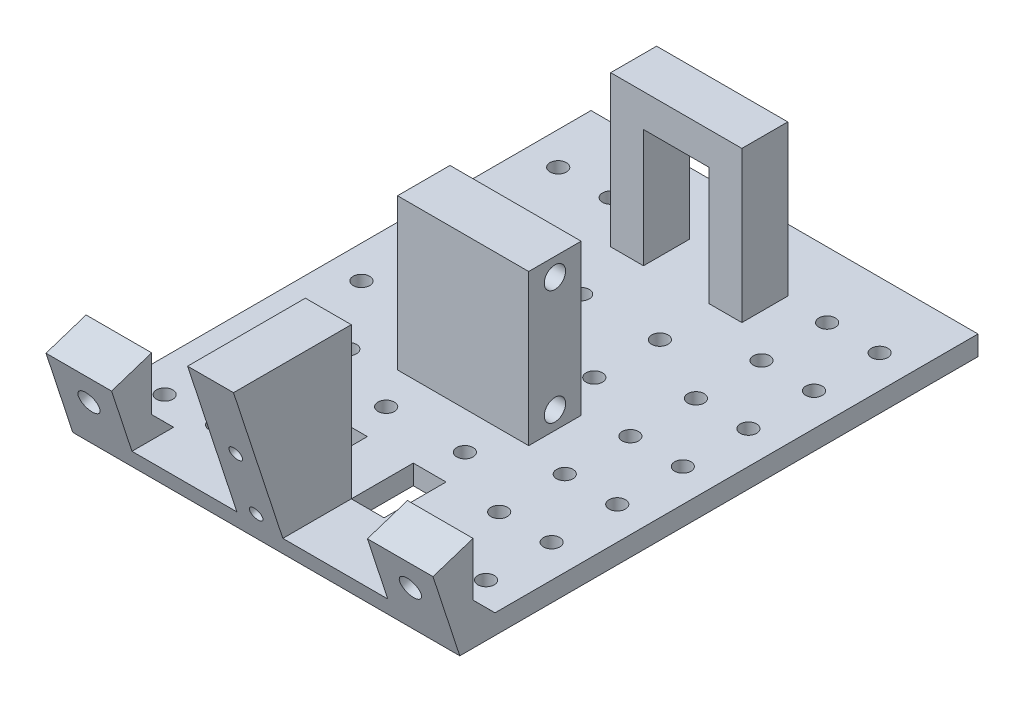
SolidWorks part; units mm, degrees
ref_plane "Alzado" through (0, 0, 0) normal (0, 0, 1) x (1, 0, 0)
ref_plane "Planta" through (0, 0, 0) normal (0, 1, 0) x (1, 0, 0)
ref_plane "Vista lateral" through (0, 0, 0) normal (1, 0, 0) x (0, 0, -1)
sketch "Croquis1" plane through (0, 0, 0) normal (0, 1, 0) x (1, 0, 0)
  line L0 (-29.5, 32.6406) -> (29.5, 32.6406)
  line L1 (29.5, 32.6406) -> (29.5, -47.3594)
  line L2 (29.5, -47.3594) -> (8.5, -47.3594)
  line L3 (8.5, -47.3594) -> (8.5, -27.4531)
  line L4 (8.5, -27.4531) -> (3.5, -27.4531)
  line L5 (3.5, -27.4531) -> (3.5, -47.3594)
  line L6 (3.5, -47.3594) -> (-3.5, -47.3594)
  line L7 (-3.5, -47.3594) -> (-3.5, -27.4531)
  line L8 (-3.5, -27.4531) -> (-8.5, -27.4531)
  line L9 (-8.5, -27.4531) -> (-8.5, -47.3594)
  line L10 (-8.5, -47.3594) -> (-29.5, -47.3594)
  line L11 (-29.5, -47.3594) -> (-29.5, 32.6406)
  line L12 (2, -7.3594) -> (47.9375, -7.3594) construction
  line L13 (0, 0) -> (0, 41.2344) construction
  dimension "D1" = 3.5
  dimension "D2" = 3.5
  dimension "D3" = 5
  dimension "D4" = 5
  dimension "D5" = 21
  dimension "D6" = 21
  dimension "D7" = 40
  dimension "D8" = 40
extrude "Saliente-Extruir1" add sketch "Croquis1" along normal blind 3
sketch "Sketch1" plane through (0, 3, 0) normal (0, 1, 0) x (1, 0, 0)
  line L0 (29.5, 32.6406) -> (-29.5, 32.6406) construction
  line L1 (-10, 23.1406) -> (10, 23.1406)
  line L2 (-10, 23.1406) -> (-10, 16.1406)
  line L3 (-10, 16.1406) -> (10, 16.1406)
  line L4 (10, 23.1406) -> (10, 16.1406)
  line L5 (-10, -8.3594) -> (10, -8.3594)
  line L6 (-10, -8.3594) -> (-10, -16.3594)
  line L7 (-10, -16.3594) -> (10, -16.3594)
  line L8 (10, -8.3594) -> (10, -16.3594)
  line L9 (0, 32.6406) -> (0, -23.7131) construction
  line L10 (8.5, -47.3594) -> (29.5, -47.3594) construction
  line L11 (3.5, -16.3594) -> (-3.5, -16.3594)
  line L12 (3.5, -16.3594) -> (3.5, -54.8594)
  line L13 (3.5, -54.8594) -> (-3.5, -54.8594)
  line L14 (-3.5, -16.3594) -> (-3.5, -54.8594)
  dimension "D1" = 9.5
  dimension "D2" = 7
  dimension "D3" = 10
  dimension "D4" = 10
  dimension "D5" = 24.5
  dimension "D6" = 8
  dimension "D7" = 10
  dimension "D8" = 10
  dimension "D9" = 7.5
extrude "Boss-Extrude1" add sketch "Sketch1" along normal blind 23 contours L9 L5 L6 L7 | L5 L9 L11 L7 L8 | L1 L9 L3 L4 | L9 L1 L2 L3
sketch "Sketch2" plane through (29.5, 0, 0) normal (1, 0, 0) x (0, 0, -1)
  line L0 (-54.8594, 26) -> (-46.3594, 0)
  line L1 (-47.3594, 0) -> (32.6406, 0) construction
  line L2 (-47.3594, 0) -> (-46.3594, 0)
  line L3 (-47.3594, 0) -> (-47.3594, 3)
  line L4 (-47.3594, 3) -> (-54.8594, 3)
  line L5 (-54.8594, 26) -> (-54.8594, 3)
  dimension "D1" = 1
extrude "Cut-Extrude1" cut sketch "Sketch2" against normal through all
sketch "Sketch3" plane through (-10, 0, 0) normal (-1, 0, 0) x (0, 0, 1)
  line L0 (8.3594, 3) -> (16.3594, 3) construction
  line L1 (16.3594, 26) -> (16.3594, 3) construction
  circle A0 centre (12.3594, 5.75) radius 1.625
  circle A1 centre (12.3594, 23.25) radius 1.625
  dimension "D1" = 3.25
  dimension "D2" = 3.25
  dimension "D3" = 2.75
  dimension "D4" = 4
  dimension "D5" = 17.5
extrude "Cut-Extrude2" cut sketch "Sketch3" against normal through all
sketch "Sketch4" plane through (0, -13.6925, 41.883) normal (0, -0.3107, 0.9505) x (1, 0, 0)
  line L0 (-3.5, 14.4057) -> (3.5, 14.4057) construction
  circle A0 centre (0, 19.4057) radius 1
  circle A1 centre (0, 29.4057) radius 1
  dimension "D1" = 2
  dimension "D2" = 2
  dimension "D3" = 5
  dimension "D4" = 10
extrude "Cut-Extrude3" cut sketch "Sketch4" against normal blind 4
sketch "Croquis2" plane through (0, 0, -23.1406) normal (0, 0, -1) x (-1, 0, 0)
  line L0 (-10, 26) -> (-10, 3) construction
  line L1 (-5, 6) -> (-5, 3)
  line L2 (-5, 6) -> (-5, 21)
  line L3 (-5, 21) -> (5, 21)
  line L4 (5, 6) -> (5, 21)
  line L5 (10, 26) -> (10, 3) construction
  line L6 (10, 26) -> (-10, 26) construction
  line L7 (10, 3) -> (-10, 3) construction
  line L8 (5, 6) -> (5, 3)
  line L9 (5, 3) -> (-5, 3)
  dimension "D1" = 5
  dimension "D2" = 5
  dimension "D3" = 5
  dimension "D4" = 3
extrude "Cortar-Extruir1" cut sketch "Croquis2" against normal blind 10
sketch "Croquis3" plane through (-3.5, 0, 0) normal (-1, 0, 0) x (0, 0, 1)
  line L1 (21.9062, 3) -> (36.9062, 3)
  line L2 (21.9062, 26) -> (16.3594, 26)
  line L3 (21.9062, 26) -> (36.9062, 26)
  line L4 (36.9062, 3) -> (36.9062, 26)
  line L5 (16.3594, 26) -> (54.8594, 26) construction
  line L7 (16.3594, 26) -> (16.3594, 3)
  line L8 (16.3594, 3) -> (21.9062, 3)
  dimension "D1" = 15
extrude "Cortar-Extruir2" cut sketch "Croquis3" against normal up to next
sketch "Croquis4" plane through (0, 0, 0) normal (0, -1, 0) x (1, 0, 0)
  line L0 (-29.5, -32.6406) -> (-29.5, 46.3594) construction
  line L1 (29.5, -32.6406) -> (-29.5, -32.6406) construction
  line L2 (0, -32.6406) -> (0, 46.3594) construction
  line L4 (-10, 8.3594) -> (10, 8.3594) construction
  circle A0 centre (-24.5, -22.6406) radius 1.25
  circle A1 centre (-16.5, -22.6406) radius 1.25
  circle A2 centre (-16.5, -12.6406) radius 1.25
  circle A3 centre (-16.5, -2.6406) radius 1.25
  circle A4 centre (-16.5, 7.3594) radius 1.25
  circle A5 centre (-16.5, 17.3594) radius 1.25
  circle A6 centre (-16.5, 27.3594) radius 1.25
  circle A7 centre (-16.5, 37.3594) radius 1.25
  circle A8 centre (-24.5, -12.6406) radius 1.25
  circle A9 centre (-24.5, -2.6406) radius 1.25
  circle A10 centre (-24.5, 7.3594) radius 1.25
  circle A11 centre (-24.5, 17.3594) radius 1.25
  circle A12 centre (-24.5, 27.3594) radius 1.25
  circle A13 centre (-24.5, 37.3594) radius 1.25
  circle A14 centre (16.5, 37.3594) radius 1.25
  circle A15 centre (24.5, 37.3594) radius 1.25
  circle A16 centre (16.5, 27.3594) radius 1.25
  circle A17 centre (24.5, 27.3594) radius 1.25
  circle A18 centre (16.5, 17.3594) radius 1.25
  circle A19 centre (24.5, 17.3594) radius 1.25
  circle A20 centre (24.5, 7.3594) radius 1.25
  circle A21 centre (16.5, 7.3594) radius 1.25
  circle A22 centre (16.5, -2.6406) radius 1.25
  circle A23 centre (24.5, -2.6406) radius 1.25
  circle A24 centre (24.5, -12.6406) radius 1.25
  circle A25 centre (16.5, -12.6406) radius 1.25
  circle A26 centre (16.5, -22.6406) radius 1.25
  circle A27 centre (24.5, -22.6406) radius 1.25
  circle A28 centre (6, 22.0845) radius 1.25
  circle A29 centre (-6, 22.0845) radius 1.25
  circle A30 centre (6, 2.3594) radius 1.25
  circle A31 centre (-6, 2.3594) radius 1.25
  circle A32 centre (-6, -7.6406) radius 1.25
  circle A33 centre (6, -7.6406) radius 1.25
  dimension "D1" = 2.5
  dimension "D6" = 2.5
  dimension "D8" = 2.5
  dimension "D2" = 5
  dimension "D3" = 10
  dimension "D7" = 6
  dimension "D9" = 6
  dimension "D4" = 2
  dimension "D5" = 7
  dimension "D10" = 2
  dimension "D11" = 2
extrude "Cortar-Extruir3" cut sketch "Croquis4" against normal up to next (3 mm away)
sketch "Sketch5" plane through (-8.5, 0, 0) normal (1, 0, 0) x (0, 0, -1)
  line L0 (-36.9062, 3) -> (-36.9062, 0)
  line L1 (-46.3594, 0) -> (32.6406, 0) construction
  line L2 (-36.9062, 0) -> (-46.3594, 0)
  line L3 (-46.3594, 0) -> (-47.3401, 3)
  line L4 (-47.3401, 3) -> (-36.9062, 3)
extrude "Boss-Extrude2" add sketch "Sketch5" along normal blind 20
sketch "Croquis6" plane through (-29.5, 0, 0) normal (-1, 0, 0) x (0, 0, 1)
  line L0 (47.3401, 3) -> (50.4475, 12.505)
  line L1 (47.3401, 3) -> (54.8594, 26) construction
  line L2 (50.4475, 12.505) -> (44.3401, 14.5016)
  line L3 (44.3401, 14.5016) -> (44.3401, 3)
  line L4 (47.3401, 3) -> (36.9062, 3) construction
  line L5 (44.3401, 3) -> (47.3401, 3)
  line L6 (44.3401, 6.348) -> (40.9901, 3)
  line L7 (-32.6406, 3) -> (47.3401, 3) construction
  line L8 (40.9901, 3) -> (44.3401, 3)
  line L9 (48.8938, 7.7525) -> (39.3394, 10.876) construction
  line L10 (44.3401, 6.348) -> (45.1947, 8.9618) construction
  line M3 (47.3401, 3) -> (-32.6406, 3)
  dimension "D1" = 10
  dimension "D2" = 3
  dimension "D3" = 2.75
  dimension "D4" = 3.348
  dimension "D5" = 3.35
extrude "Saliente-Extruir2" add sketch "Croquis6" against normal blind 10 contours L2 L3 L0 M3 | L3 L6 M3
sketch "Croquis7" plane through (0, -13.6925, 41.883) normal (0, -0.3107, 0.9505) x (1, 0, 0)
  circle A0 centre (-24.5, 22.5619) radius 1.625
  dimension "D1" = 3.25
extrude "Cortar-Extruir4" cut sketch "Croquis7" against normal up to next
sketch "Croquis8" plane through (0, -13.6925, 41.883) normal (0, -0.3107, 0.9505) x (1, 0, 0)
  line L1 (-22.9123, 19.8119) -> (-21.3246, 22.5619)
  line L2 (-21.3246, 22.5619) -> (-22.9123, 25.3119)
  line L3 (-22.9123, 25.3119) -> (-26.0877, 25.3119)
  line L4 (-26.0877, 25.3119) -> (-27.6754, 22.5619)
  line L5 (-27.6754, 22.5619) -> (-26.0877, 19.8119)
  line L6 (-26.0877, 19.8119) -> (-22.9123, 19.8119)
  circle A0 centre (-24.5, 22.5619) radius 2.75 construction
  dimension "D1" = 5.5
extrude "Cortar-Extruir5" cut sketch "Croquis8" along normal blind 4 from vertex at -6.4255 starting at point (-29.5, 14.5016, 44.3401)
sketch "Croquis9" plane through (29.5, 0, 0) normal (1, 0, 0) x (0, 0, -1)
  line L0 (-47.3401, 3) -> (-50.4475, 12.505)
  line L1 (-54.8594, 26) -> (-47.3401, 3) construction
  line L2 (-50.4475, 12.505) -> (-44.3401, 14.5016)
  line L3 (-44.3401, 14.5016) -> (-44.3401, 3)
  line L4 (-36.9062, 3) -> (-47.3401, 3) construction
  line L5 (-44.3401, 3) -> (-47.3401, 3)
  line L6 (-48.8938, 7.7525) -> (-43.2719, 9.5904) construction
  line L7 (-44.3401, 6.348) -> (-40.9901, 3)
  line L8 (-40.9901, 3) -> (-44.3401, 3)
  line L9 (-44.3401, 6.348) -> (-45.1947, 8.9618) construction
  line M1 (32.6406, 3) -> (-47.3401, 3)
  dimension "D1" = 10
  dimension "D2" = 3
  dimension "D3" = 2.75
  dimension "D4" = 5
  dimension "D5" = 3.348
  dimension "D6" = 3.35
extrude "Saliente-Extruir3" add sketch "Croquis9" against normal blind 10 contours L3 L2 L0 M1 | L7 L3 M1
sketch "Croquis10" plane through (0, -13.6925, 41.883) normal (0, -0.3107, 0.9505) x (1, 0, 0)
  circle A0 centre (24.5, 22.5619) radius 1.625
  dimension "D1" = 3.25
extrude "Cortar-Extruir6" cut sketch "Croquis10" against normal up to next
sketch "Croquis11" plane through (0, -13.6925, 41.883) normal (0, -0.3107, 0.9505) x (1, 0, 0)
  line L1 (26.0877, 19.8119) -> (27.6754, 22.5619)
  line L2 (27.6754, 22.5619) -> (26.0877, 25.3119)
  line L3 (26.0877, 25.3119) -> (22.9123, 25.3119)
  line L4 (22.9123, 25.3119) -> (21.3246, 22.5619)
  line L5 (21.3246, 22.5619) -> (22.9123, 19.8119)
  line L6 (22.9123, 19.8119) -> (26.0877, 19.8119)
  circle A0 centre (24.5, 22.5619) radius 2.75 construction
  dimension "D1" = 5.5
extrude "Cortar-Extruir7" cut sketch "Croquis11" along normal blind 4 from vertex at -2.4255
